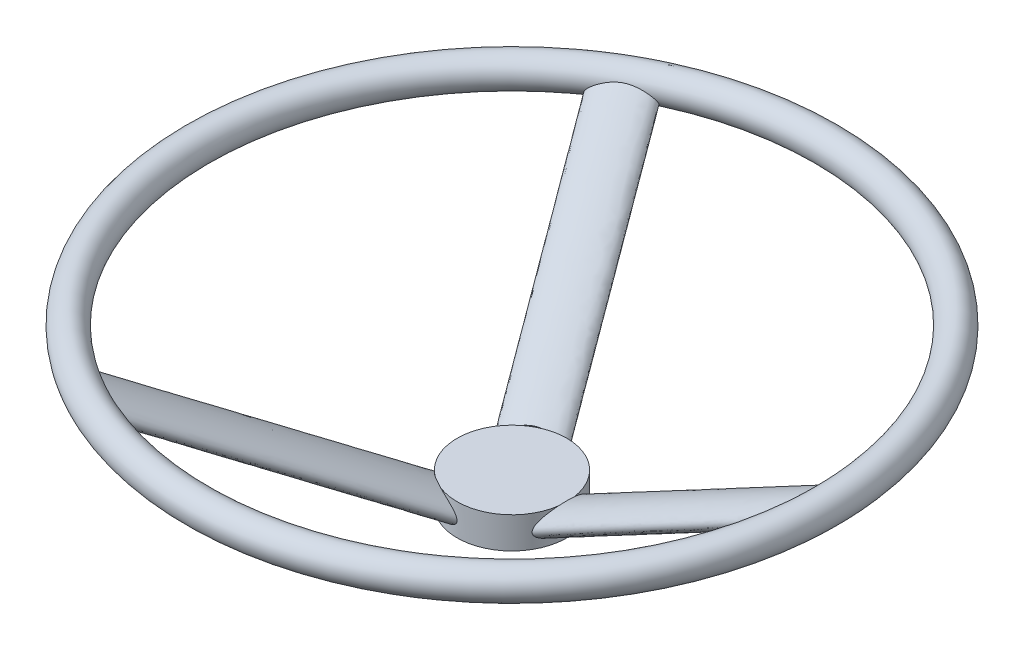
SolidWorks part; units mm, degrees
ref_plane "Front Plane" through (0, 0, 0) normal (0, 0, 1) x (1, 0, 0)
ref_plane "Top Plane" through (0, 0, 0) normal (0, 1, 0) x (1, 0, 0)
ref_plane "Right Plane" through (0, 0, 0) normal (1, 0, 0) x (0, 0, -1)
sketch "Sketch1" plane through (0, 0, 0) normal (0, 0, 1) x (1, 0, 0)
  line L1 (0, 0) -> (35, 0)
  line L2 (0, 0) -> (0, 20)
  line L3 (0, 20) -> (35, 20)
  line L4 (35, 0) -> (35, 20)
  circle A0 centre (200, 100) radius 10
  dimension "D3" = 20
  dimension "D1" = 20
  dimension "D2" = 35
  dimension "D4" = 200
  dimension "D5" = 100
revolve "Revolve1" add sketch "Sketch1" angle 360 about L2
sketch "Sketch2" plane through (0, 0, 0) normal (0, 0, 1) x (1, 0, 0)
  line L0 (35, 12) -> (200, 100)
  line L1 (35, 0) -> (35, 20) construction
  line L2 (35, 20) -> (-35, 20) construction
  arc A0 (200, 90) -> (200, 110) centre (200, 100) ccw construction
  dimension "D1" = 8
  dimension "D2" = 0
ref_plane "Plane1" through (200, 100, 0) normal (0.8824, 0.4706, 0) x (0.4706, -0.8824, 0)
sketch "Sketch3" plane through (200, 100, 0) normal (0.8824, 0.4706, 0) x (0.4706, -0.8824, 0)
  ellipse E0 centre (-0.0392, 0) end of major axis (-0.0392, 17.5) minor radius 7.5
  dimension "D1" = 35
  dimension "D2" = 15
extrude "Boss-Extrude1" add sketch "Sketch3" against normal up to surface (192.2934 mm away)
pattern_circular "CirPattern1" count 3 every 120 about axis through (0, 20, 0) along (0, -1, 0) of "Boss-Extrude1"
